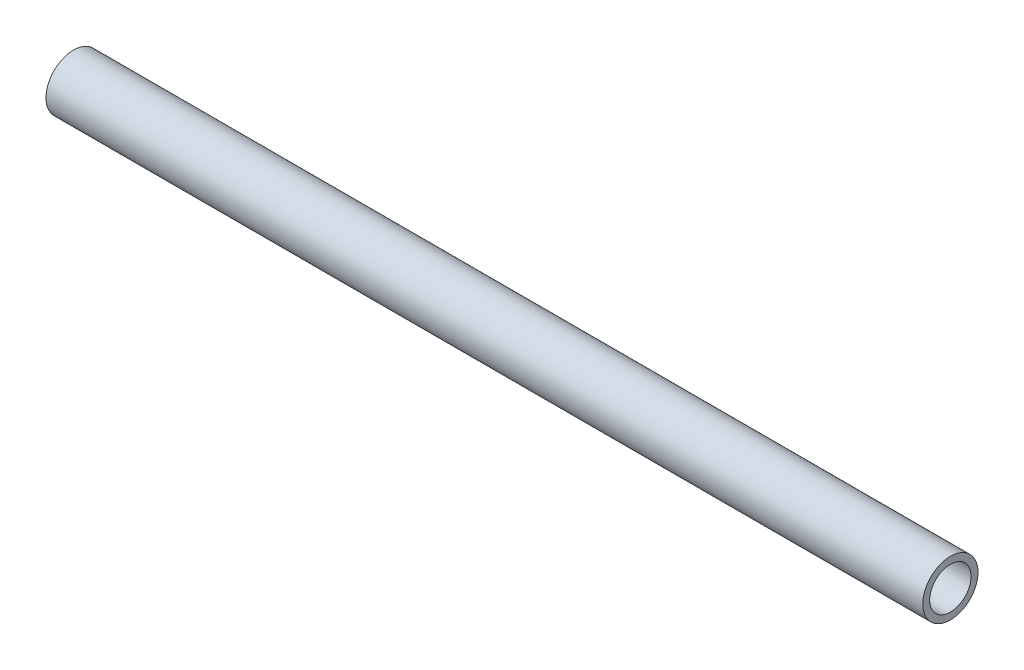
SolidWorks part; units mm, degrees
ref_plane "Front Plane" through (0, 0, 0) normal (0, 0, 1) x (1, 0, 0)
ref_plane "Top Plane" through (0, 0, 0) normal (0, 1, 0) x (1, 0, 0)
ref_plane "Right Plane" through (0, 0, 0) normal (1, 0, 0) x (0, 0, -1)
sketch3d "3DSketch1"
  line L0 (0, 0, 0) -> (127, 0, 0)
  dimension "D1" = 127
sketch "Sketch1" plane through (0, 0, 0) normal (1, 0, 0) x (0, 0, -1)
  circle A0 centre (0, 0) radius 4
  circle A1 centre (0, 0) radius 3
  dimension "D1" = 8
  dimension "D2" = 6
sweep "Sweep1" add profiles "Sketch1" path "3DSketch1"
